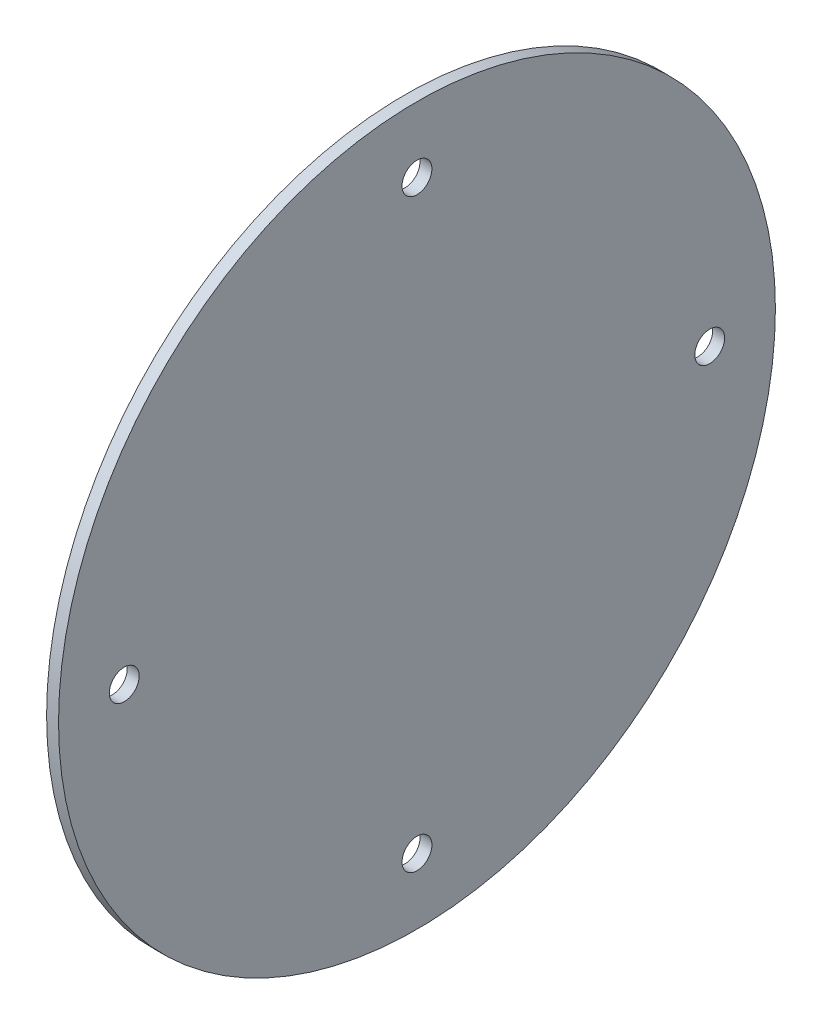
SolidWorks part; units mm, degrees
ref_plane "Front Plane" through (0, 0, 0) normal (1, 0, 0) x (0, 1, 0)
ref_plane "Top Plane" through (0, 0, 0) normal (0, 0, 1) x (0, 1, 0)
ref_plane "Right Plane" through (0, 0, 0) normal (0, 1, 0) x (-1, 0, 0)
sketch "Sketch1" plane through (0, 0, 0) normal (1, 0, 0) x (0, 1, 0)
  circle A0 centre (0, 0) radius 76.2
  dimension "D1" = 152.4
extrude "Boss-Extrude1" add sketch "Sketch1" along normal blind 2.54
sketch "Sketch2" plane through (2.54, 0, 0) normal (1, 0, 0) x (0, 0, -1)
  line L0 (0, 0) -> (-62.23, 0)
  circle A0 centre (-62.23, 0) radius 3.175
  dimension "D2" = 6.35
  dimension "D1" = 62.23
extrude "Cut-Extrude2" cut sketch "Sketch2" against normal through all contours A0
pattern_circular "CirPattern2" count 4 over 360 about axis through (0, 0, 0) along (1, 0, 0) of "Cut-Extrude2"
